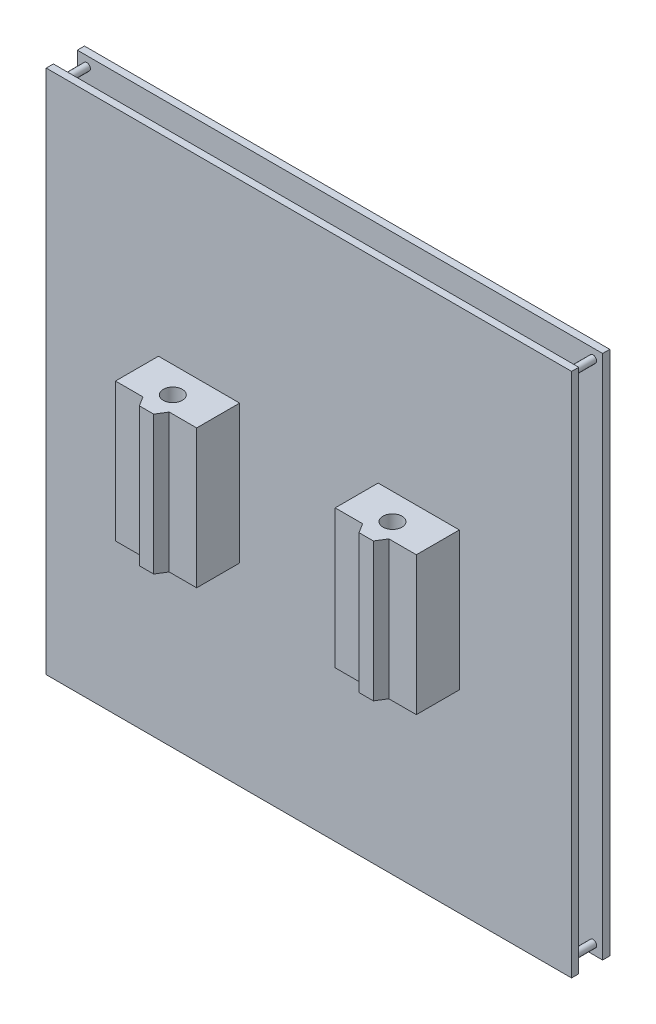
SolidWorks part; units mm, degrees
ref_plane "前基準面" through (0, 0, 0) normal (0, 0, 1) x (1, 0, 0)
ref_plane "上基準面" through (0, 0, 0) normal (0, 1, 0) x (1, 0, 0)
ref_plane "右基準面" through (0, 0, 0) normal (1, 0, 0) x (0, 0, -1)
sketch "草圖1" plane through (0, 0, 0) normal (0, 0, 1) x (1, 0, 0)
  line L1 (-110, 110) -> (110, 110)
  line L2 (-110, 110) -> (-110, -110)
  line L3 (-110, -110) -> (110, -110)
  line L4 (110, 110) -> (110, -110)
  point P4 (0, 110)
  point P6 (-110, 0)
  dimension "D1" = 220
  dimension "D2" = 220
extrude "填料-伸長1" add sketch "草圖1" along normal blind 3
sketch "草圖2" plane through (0, 0, 3) normal (0, 0, 1) x (1, 0, 0)
  line L0 (110, 110) -> (-110, 110) construction
  line L1 (-110, 110) -> (-110, -110) construction
  circle A0 centre (-106, 106) radius 1.5
  circle A1 centre (106, 106) radius 1.5
  circle A2 centre (106, -106) radius 1.5
  circle A3 centre (-106, -106) radius 1.5
  point P15 (0, 0)
  dimension "D1" = 3
  dimension "D2" = 4
  dimension "D3" = 4
  dimension "D4" = 4
extrude "填料-伸長2" add sketch "草圖2" along normal blind 10
sketch "草圖3" plane through (0, 0, 13) normal (0, 0, 1) x (1, 0, 0)
  line L1 (-110, 110) -> (110, 110)
  line L2 (-110, 110) -> (-110, -110)
  line L3 (-110, -110) -> (110, -110)
  line L4 (110, 110) -> (110, -110)
extrude "填料-伸長3" add sketch "草圖3" along normal blind 3
sketch "草圖4" plane through (0, 0, 16) normal (0, 0, 1) x (1, 0, 0)
  line L0 (0, 110) -> (0, -110) construction
  line L1 (110, 110) -> (-110, 110) construction
  line L2 (-110, -110) -> (110, -110) construction
  line L3 (-46, 29) -> (-46, -29) construction
  line L4 (-63, 29) -> (-29, 29)
  line L5 (-63, 29) -> (-63, -29)
  line L6 (-63, -29) -> (-29, -29)
  line L7 (-29, 29) -> (-29, -29)
  point P5 (-46, 0)
  point P11 (-29, 0)
  dimension "D1" = 34
  dimension "D2" = 58
  dimension "D3" = 29
  dimension "D4" = 46
extrude "填料-伸長4" add sketch "草圖4" along normal blind 22
sketch "草圖5" plane through (0, 29, 0) normal (0, 1, 0) x (1, 0, 0)
  line L0 (-63, -38) -> (-63, -16) construction
  line L1 (-29, -38) -> (-63, -38) construction
  line L2 (-29, -16) -> (-63, -16) construction
  line L3 (-63, -34) -> (-51.5, -34)
  line L4 (-51.5, -34) -> (-49, -38)
  line L5 (-49, -38) -> (-63, -38)
  line L6 (-63, -38) -> (-63, -34)
  line L7 (-51.5, -27) -> (-51.5, -38) construction
  line L8 (-46, -16) -> (-46, -38) construction
  line L9 (-29, -38) -> (-29, -34)
  line L10 (-43, -38) -> (-29, -38)
  line L11 (-40.5, -34) -> (-43, -38)
  line L12 (-29, -34) -> (-40.5, -34)
  circle A0 centre (-46, -27) radius 4
  circle A1 centre (-46, -27) radius 5.5 construction
  point P5 (-63, -27)
  point P8 (-46, -38)
  dimension "D1" = 8
  dimension "D2" = 18
  dimension "D4" = 11
  dimension "D3" = 11
  dimension "D5" = 3
  dimension "D6" = 4
extrude "除料-伸長1" cut sketch "草圖5" against normal through all both and the other way through all
mirror "鏡射1" about plane through (0, 0, 0) normal (1, 0, 0) of "填料-伸長4", "除料-伸長1"
sketch "草圖6" plane through (0, 0, 0) normal (0, 0, -1) x (-1, 0, 0)
  line L1 (100, -100) -> (-100, -100)
  line L2 (100, -100) -> (100, 100)
  line L3 (100, 100) -> (-100, 100)
  line L4 (-100, -100) -> (-100, 100)
  point P4 (0, -100)
  point P6 (100, 0)
  dimension "D1" = 200
  dimension "D2" = 200
